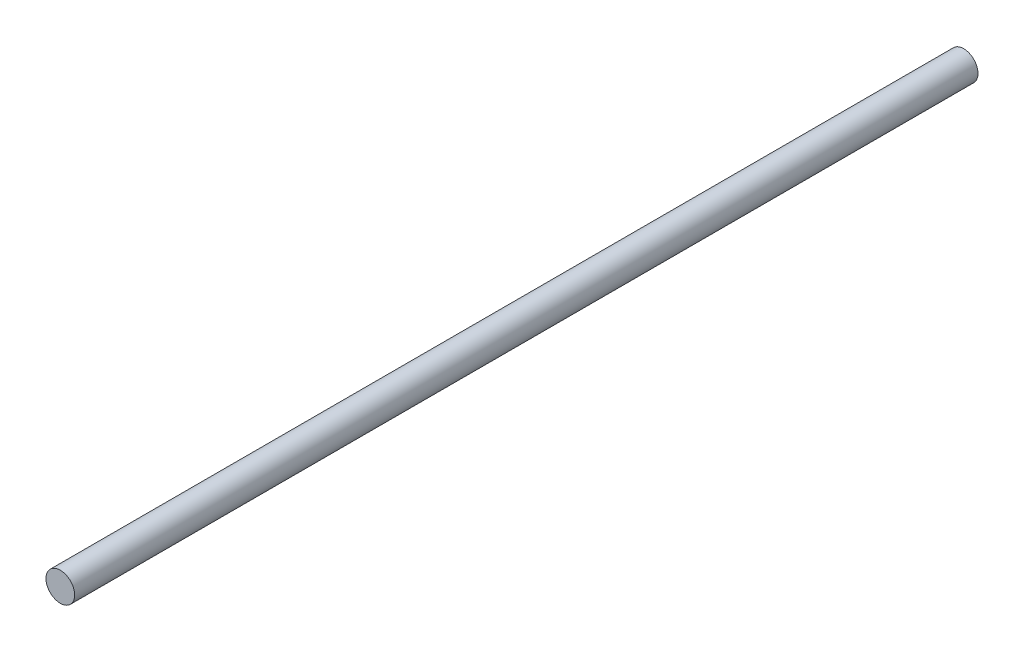
SolidWorks part; units mm, degrees
ref_plane "Front Plane" through (0, 0, 0) normal (0, 0, 1) x (1, 0, 0)
ref_plane "Top Plane" through (0, 0, 0) normal (0, 1, 0) x (1, 0, 0)
ref_plane "Right Plane" through (0, 0, 0) normal (1, 0, 0) x (0, 0, -1)
sketch "Sketch1" plane through (0, 0, 0) normal (0, 0, 1) x (1, 0, 0)
  circle A0 centre (0, 0) radius 3.175
  dimension "D1" = 6.35
extrude "Boss-Extrude1" add sketch "Sketch1" along normal blind 200
ref_plane "Plane1" through (0, 0, 100) normal (0, 0, 1) x (1, 0, 0)
